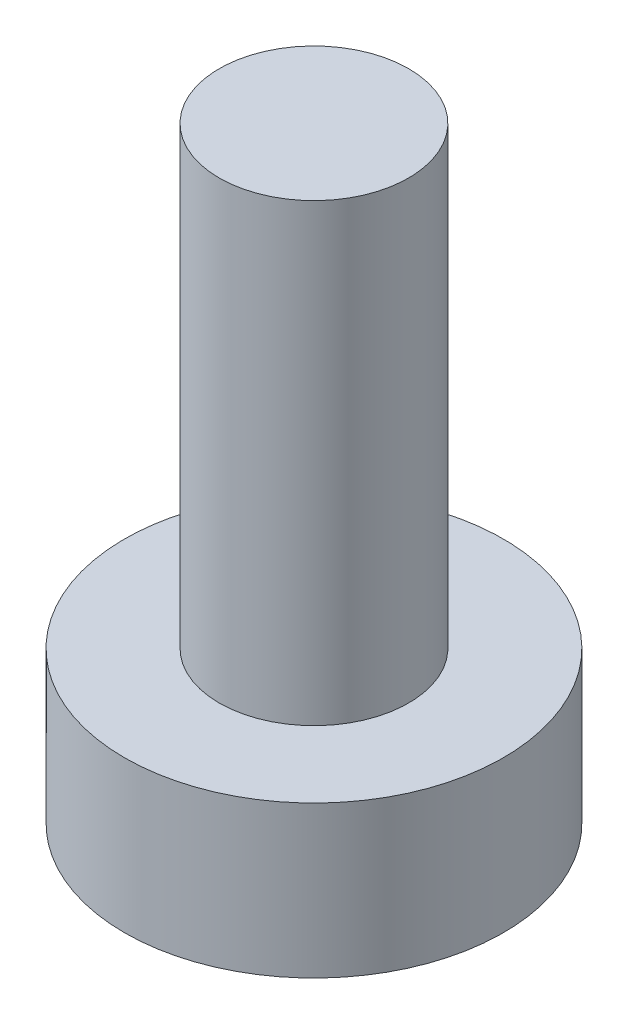
SolidWorks part; units mm, degrees
ref_plane "前视基准面" through (0, 0, 0) normal (0, 0, 1) x (1, 0, 0)
ref_plane "上视基准面" through (0, 0, 0) normal (0, 1, 0) x (1, 0, 0)
ref_plane "右视基准面" through (0, 0, 0) normal (1, 0, 0) x (0, 0, -1)
sketch "草图1" plane through (0, 0, 0) normal (0, 1, 0) x (1, 0, 0)
  circle A0 centre (0, 0) radius 5
  dimension "D1" = 10
extrude "凸台-拉伸1" add sketch "草图1" along normal blind 4
sketch "草图2" plane through (0, 4, 0) normal (0, 1, 0) x (1, 0, 0)
  circle A0 centre (0, 0) radius 2.5
  dimension "D1" = 5
extrude "凸台-拉伸2" add sketch "草图2" along normal blind 12
sketch "草图3" plane through (0, 0, 0) normal (0, -1, 0) x (1, 0, 0)
  line L1 (-3.4641, 0) -> (-1.7321, -3)
  line L2 (-1.7321, -3) -> (1.7321, -3)
  line L3 (1.7321, -3) -> (3.4641, 0)
  line L4 (3.4641, 0) -> (1.7321, 3)
  line L5 (1.7321, 3) -> (-1.7321, 3)
  line L6 (-1.7321, 3) -> (-3.4641, 0)
  circle A0 centre (0, 0) radius 3 construction
  dimension "D1" = 6
extrude "切除-拉伸1" cut sketch "草图3" against normal blind 1
